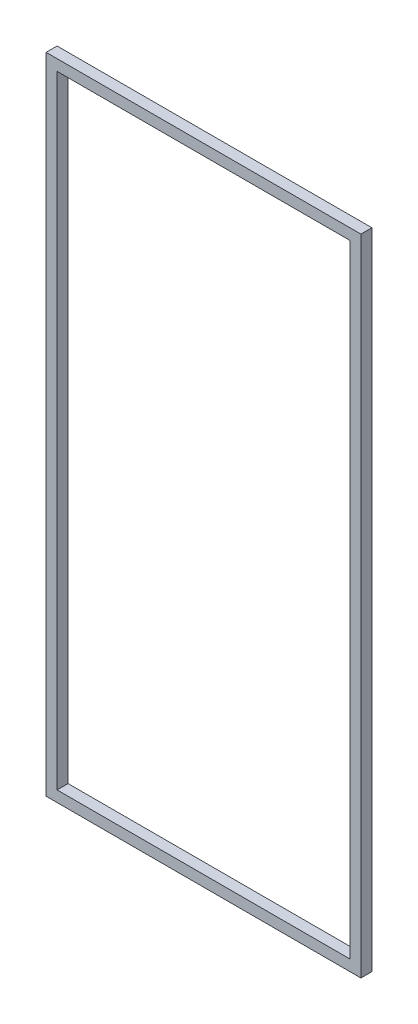
SolidWorks part; units mm, degrees
ref_plane "前视基准面" through (0, 0, 0) normal (0, 0, 1) x (1, 0, 0)
ref_plane "上视基准面" through (0, 0, 0) normal (0, 1, 0) x (1, 0, 0)
ref_plane "右视基准面" through (0, 0, 0) normal (1, 0, 0) x (0, 0, -1)
sketch "草图1" plane through (0, 0, 0) normal (0, 0, 1) x (1, 0, 0)
  line L0 (0, 25.9622) -> (0, -25.1544) construction
  line L1 (24.4237, 0) -> (-27.6453, 0) construction
  line L3 (-200, 425) -> (200, 425)
  line L4 (-200, 425) -> (-200, -425)
  line L5 (-200, -425) -> (200, -425)
  line L6 (200, 425) -> (200, -425)
  line L7 (-200, 425) -> (200, -425) construction
  line L8 (-200, -425) -> (200, 425) construction
  point P5 (0, 0)
  dimension "D1" = 400
  dimension "D2" = 850
extrude "拉伸-薄壁1" add sketch "草图1" along normal blind 15 thin thin type one direction wall 15
sketch "草图4" plane through (0, 425, 0) normal (0, -1, 0) x (1, 0, 0)
  line L0 (-155, 15) -> (-155, 0)
  line L1 (-215, 15) -> (215, 15) construction
  line L2 (-215, 0) -> (215, 0) construction
  line L3 (-155, 0) -> (-170, 0)
  line L4 (-170, 0) -> (-170, 15)
  line L5 (-170, 15) -> (-155, 15)
  line L6 (155, 15) -> (155, 0)
  line L7 (155, 0) -> (170, 0)
  line L8 (170, 0) -> (170, 15)
  line L9 (170, 15) -> (155, 15)
  dimension "D1" = 60
  dimension "D2" = 15
  dimension "D3" = 60
  dimension "D4" = 15
